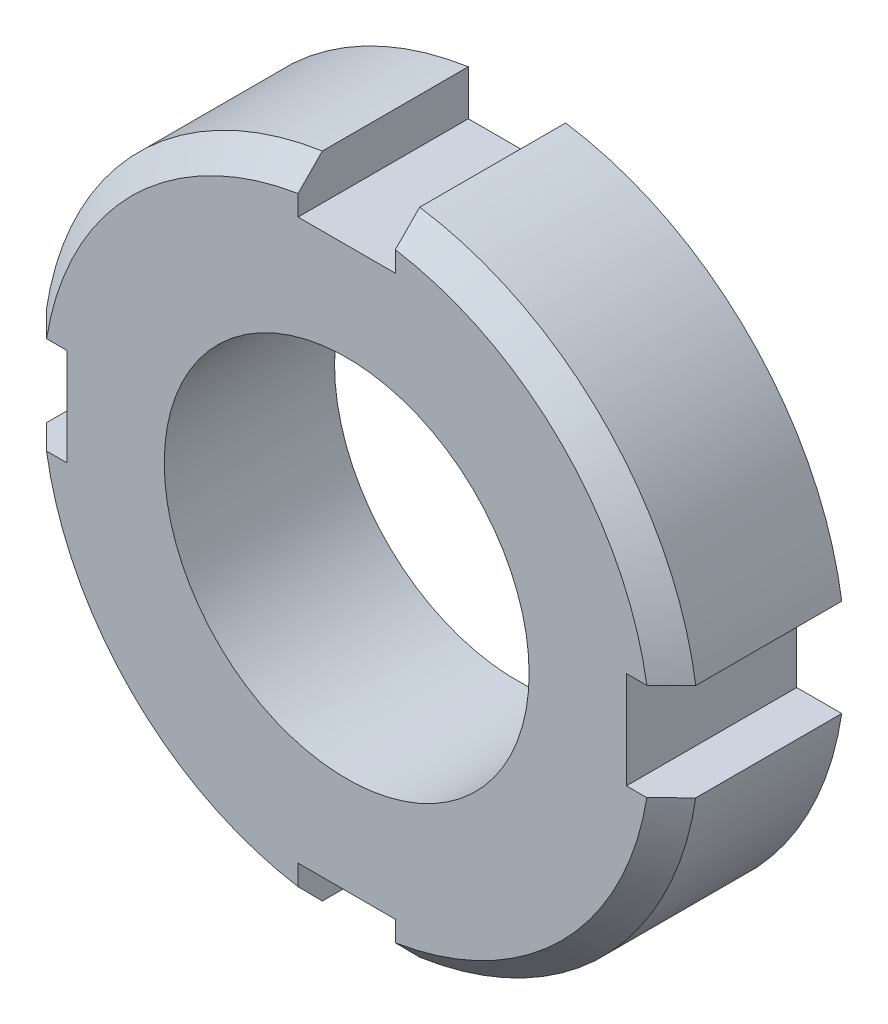
SolidWorks part; units mm, degrees
ref_plane "Front Plane" through (0, 0, 0) normal (0, 0, 1) x (1, 0, 0)
ref_plane "Top Plane" through (0, 0, 0) normal (0, 1, 0) x (1, 0, 0)
ref_plane "Right Plane" through (0, 0, 0) normal (1, 0, 0) x (0, 0, -1)
sketch "Sketch2" plane through (0, 0, 0) normal (0, 0, 1) x (1, 0, 0)
  circle A0 centre (0, 0) radius 13.5
  dimension "D1" = 27
extrude "Boss-Extrude1" add sketch "Sketch2" along normal blind 7
sketch "Sketch3" plane through (0, 0, 7) normal (0, 0, 1) x (1, 0, 0)
  circle A0 centre (0, 0) radius 7.5
  dimension "D1" = 15
extrude "Cut-Extrude1" cut sketch "Sketch3" against normal through all
sketch "Sketch4" plane through (0, 0, 7) normal (0, 0, 1) x (1, 0, 0)
  line L0 (0, 15.4517) -> (0, 0) construction
  line L1 (15.5, 2) -> (11.5, 2)
  line L2 (-2, 15.5) -> (2, 15.5)
  line L3 (-2, 15.5) -> (-2, 11.5)
  line L4 (-2, 11.5) -> (2, 11.5)
  line L5 (2, 15.5) -> (2, 11.5)
  line L6 (-2, 15.5) -> (2, 11.5) construction
  line L7 (-2, 11.5) -> (2, 15.5) construction
  line L8 (15.5, 2) -> (15.5, -2)
  line L9 (11.5, 2) -> (11.5, -2)
  line L10 (15.5, -2) -> (11.5, -2)
  line L11 (2, -15.5) -> (2, -11.5)
  line L12 (2, -15.5) -> (-2, -15.5)
  line L13 (2, -11.5) -> (-2, -11.5)
  line L14 (-2, -15.5) -> (-2, -11.5)
  line L15 (-15.5, -2) -> (-11.5, -2)
  line L16 (-15.5, -2) -> (-15.5, 2)
  line L17 (-11.5, -2) -> (-11.5, 2)
  line L18 (-15.5, 2) -> (-11.5, 2)
  circle A0 centre (0, 0) radius 13.5 construction
  point P3 (0, 13.5)
  point P25 (0, 0)
  dimension "D1" = 4
  dimension "D2" = 2
  dimension "D3" = 4
extrude "Cut-Extrude2" cut sketch "Sketch4" against normal through all
chamfer "Chamfer1" distance 1 angle 45 4 edges at (9.5459, 9.5459, 7) (9.5459, -9.5459, 7) (-9.5459, -9.5459, 7) (-9.5459, 9.5459, 7)
